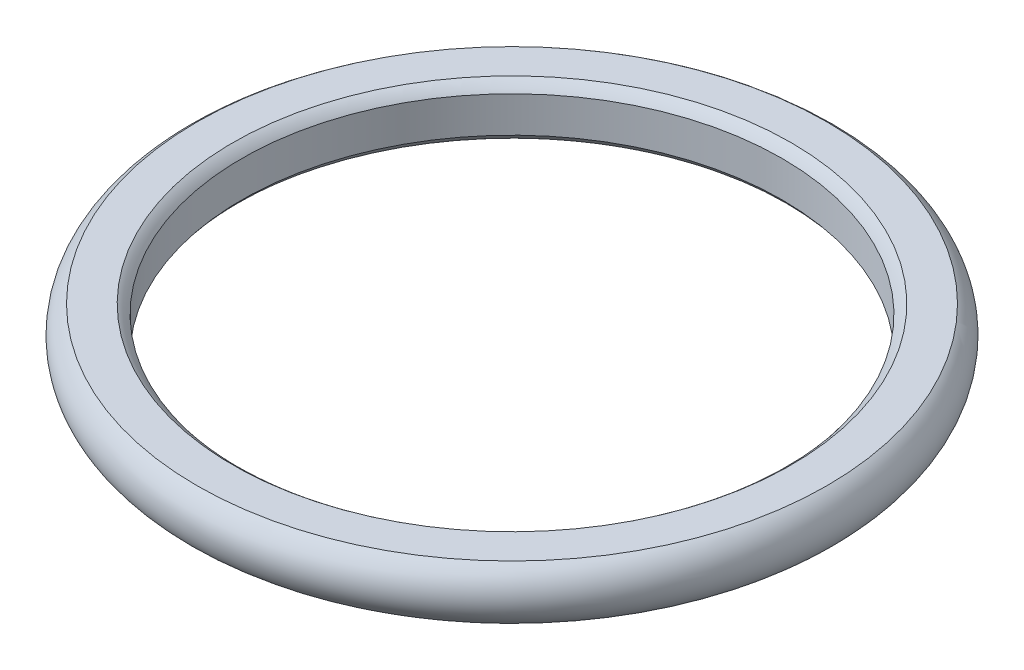
SolidWorks part; units mm, degrees
material "ｺﾞﾑ"
ref_plane "正面" through (0, 0, 0) normal (0, 0, 1) x (1, 0, 0)
ref_plane "平面" through (0, 0, 0) normal (0, 1, 0) x (1, 0, 0)
ref_plane "右側面" through (0, 0, 0) normal (1, 0, 0) x (0, 0, -1)
sketch "ｽｹｯﾁ2" plane through (0, 0, 0) normal (0, 0, 1) x (1, 0, 0)
  line L0 (0, 0) -> (0, 13.2257) construction
  circle A0 centre (27.5, 0) radius 3
  dimension "D1" = 6
  dimension "D2" = 27.5
  dimension "D3" = 0
revolve "回転1" add sketch "ｽｹｯﾁ2" angle 360 about L0
sketch "ｽｹｯﾁ3" plane through (0, 0, 0) normal (0, 1, 0) x (1, 0, 0)
  circle A0 centre (0, 0) radius 25
  dimension "D1" = 50
extrude "ｶｯﾄ - 押し出し1" cut sketch "ｽｹｯﾁ3" against normal mid plane 10
ref_plane "平面1" through (0, 2.5, 0) normal (0, 1, 0) x (1, 0, 0)
sketch "ｽｹｯﾁ4" plane through (0, 2.5, 0) normal (0, 1, 0) x (1, 0, 0)
  circle A0 centre (0, 0) radius 35
  dimension "D1" = 70
extrude "ｶｯﾄ - 押し出し2" cut sketch "ｽｹｯﾁ4" along normal blind 10
